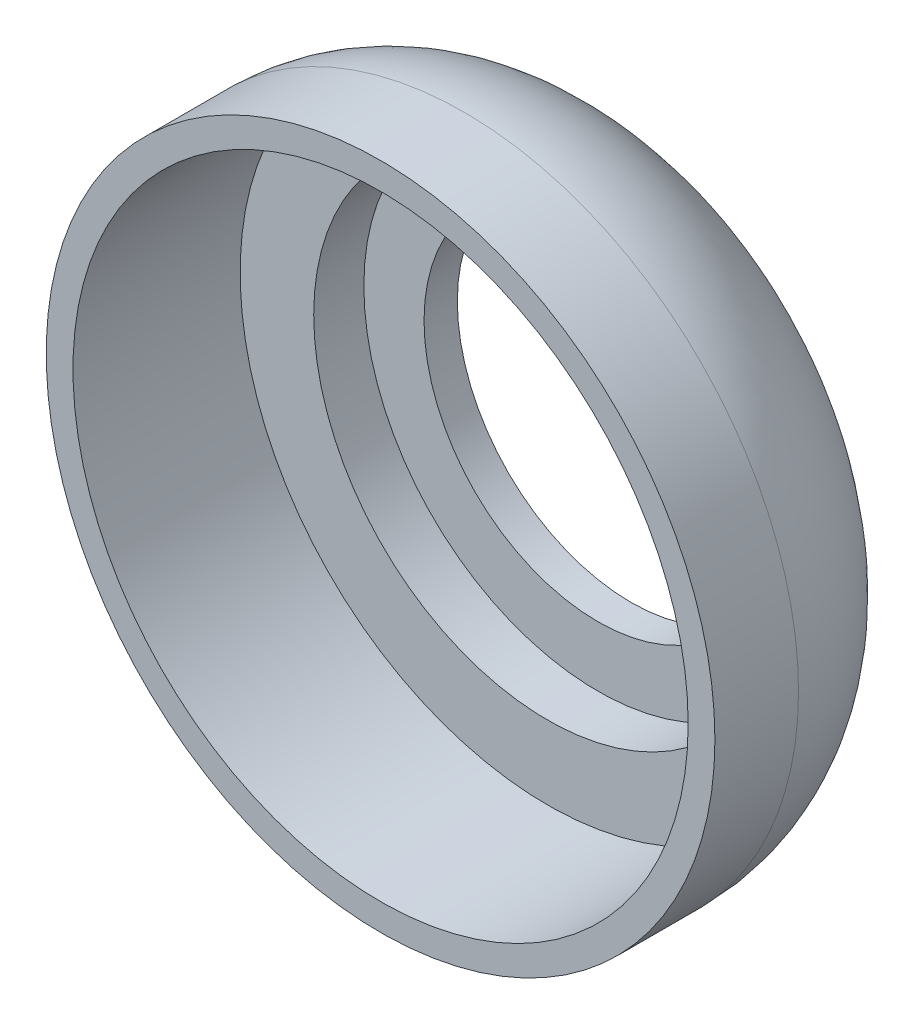
SolidWorks part; units mm, degrees
ref_plane "Front Plane" through (0, 0, 0) normal (0, 0, 1) x (1, 0, 0)
ref_plane "Top Plane" through (0, 0, 0) normal (0, 1, 0) x (1, 0, 0)
ref_plane "Right Plane" through (0, 0, 0) normal (1, 0, 0) x (0, 0, -1)
sketch "Sketch1" plane through (0, 0, 0) normal (0, 0, 1) x (1, 0, 0)
  circle A0 centre (0, 0) radius 20
  dimension "D1" = 40
extrude "Boss-Extrude1" add sketch "Sketch1" along normal blind 15
fillet "Fillet1" radius 10 1 edges at (20, 0, 0)
sketch "Sketch2" plane through (0, 0, 15) normal (0, 0, 1) x (1, 0, 0)
  circle A0 centre (0, 0) radius 14
  dimension "D1" = 28
extrude "Cut-Extrude1" cut sketch "Sketch2" against normal blind 13
sketch "Sketch3" plane through (0, 0, 15) normal (0, 0, 1) x (1, 0, 0)
  circle A0 centre (0, 0) radius 18.4
  dimension "D1" = 36.8
sketch "Sketch4" plane through (0, 0, 0) normal (0, 0, -1) x (-1, 0, 0)
  circle A0 centre (0, 0) radius 10.4
  dimension "D1" = 20.8
extrude "Cut-Extrude3" cut sketch "Sketch4" against normal blind 11
extrude "Cut-Extrude4" cut sketch "Sketch3" against normal blind 10
